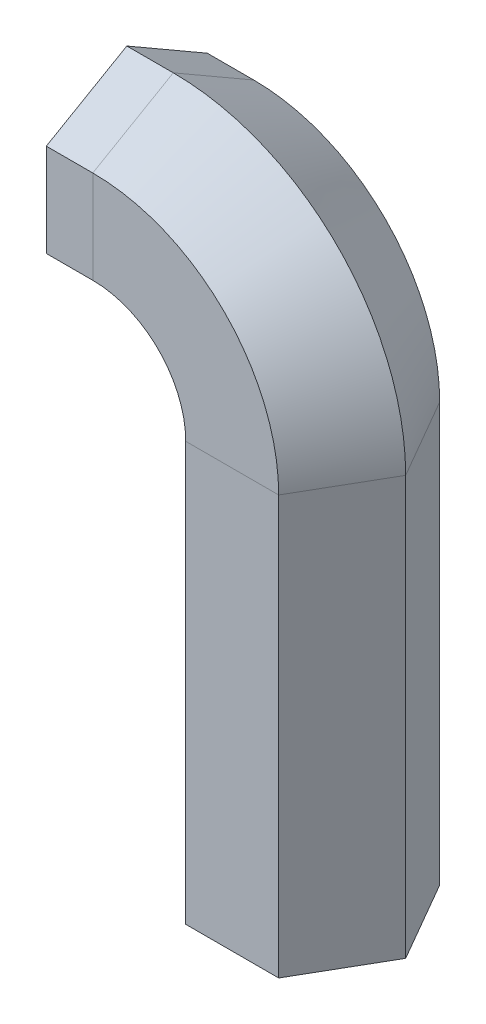
SolidWorks part; units mm, degrees
ref_plane "Front Plane" through (0, 0, 0) normal (0, 0, 1) x (1, 0, 0)
ref_plane "Top Plane" through (0, 0, 0) normal (0, 1, 0) x (1, 0, 0)
ref_plane "Right Plane" through (0, 0, 0) normal (1, 0, 0) x (0, 0, -1)
sketch "Sketch2" plane through (0, 0, 0) normal (0, 1, 0) x (1, 0, 0)
  line L1 (10, -17.3205) -> (20, 0)
  line L2 (20, 0) -> (10, 17.3205)
  line L3 (10, 17.3205) -> (-10, 17.3205)
  line L4 (-10, 17.3205) -> (-20, 0)
  line L5 (-20, 0) -> (-10, -17.3205)
  line L6 (-10, -17.3205) -> (10, -17.3205)
  circle A0 centre (0, 0) radius 17.3205 construction
  dimension "D1" = 20
sketch "Sketch5" plane through (0, 0, 0) normal (0, 0, 1) x (1, 0, 0)
  line L0 (0, 0) -> (0, 90)
  line L1 (17.3205, 0) -> (-17.3205, 0) construction
  line L2 (-30, 120) -> (-40, 120)
  arc A0 (0, 90) -> (-30, 120) centre (-30, 90) ccw
  point P7 (0, 120)
  dimension "D3" = 30
  dimension "D1" = 120
  dimension "D2" = 40
sweep "Sweep3" add profiles "Sketch2" path "Sketch5"
